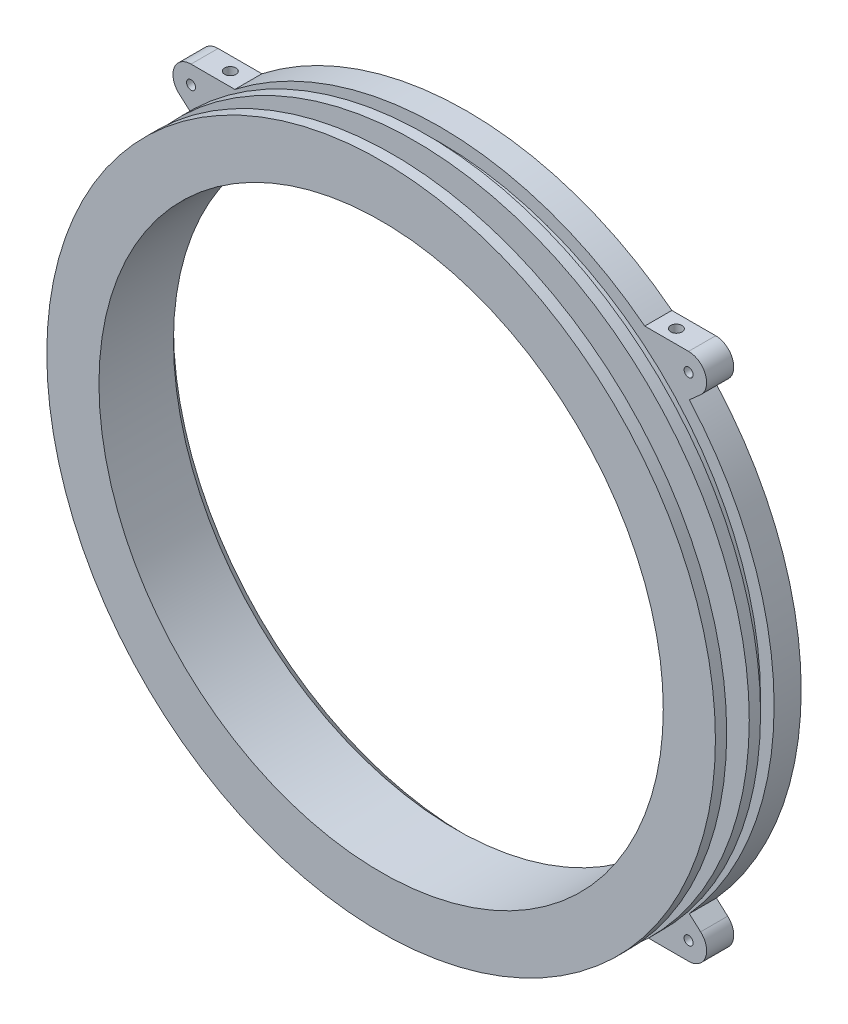
SolidWorks part; units mm, degrees
ref_plane "前视基准面" through (0, 0, 0) normal (0, 0, 1) x (1, 0, 0)
ref_plane "上视基准面" through (0, 0, 0) normal (0, 1, 0) x (1, 0, 0)
ref_plane "右视基准面" through (0, 0, 0) normal (1, 0, 0) x (0, 0, -1)
sketch "草图1" plane through (0, 0, 0) normal (0, 0, 1) x (1, 0, 0)
  circle A0 centre (0, 0) radius 148.1
  circle A1 centre (0, 0) radius 125
  dimension "D1" = 296.2
  dimension "D2" = 250
extrude "凸台-拉伸1" add sketch "草图1" along normal blind 12
sketch "草图2" plane through (0, 0, 12) normal (0, 0, 1) x (1, 0, 0)
  circle A0 centre (0, 0) radius 125
  circle A1 centre (0, 0) radius 142.1
  circle A2 centre (0, 0) radius 125 construction
  circle A3 centre (0, 0) radius 148.1 construction
  dimension "D1" = 6
extrude "凸台-拉伸2" add sketch "草图2" along normal blind 6
sketch "草图3" plane through (0, 0, 18) normal (0, 0, 1) x (1, 0, 0)
  circle A0 centre (0, 0) radius 125
  circle A1 centre (0, 0) radius 148.1
  circle A2 centre (0, 0) radius 125 construction
  circle A3 centre (0, 0) radius 148.1 construction
extrude "凸台-拉伸3" add sketch "草图3" along normal blind 5
sketch "草图4" plane through (0, 0, 23) normal (0, 0, 1) x (1, 0, 0)
  circle A0 centre (0, 0) radius 125
  circle A1 centre (0, 0) radius 133.1
  circle A2 centre (0, 0) radius 148.1 construction
  circle A4 centre (0, 0) radius 125 construction
  dimension "D1" = 15
extrude "凸台-拉伸4" add sketch "草图4" along normal blind 10
sketch "草图5" plane through (0, 0, 33) normal (0, 0, 1) x (1, 0, 0)
  circle A0 centre (0, 0) radius 125
  circle A1 centre (0, 0) radius 148.1
  circle A2 centre (0, 0) radius 125 construction
  circle A3 centre (0, 0) radius 148.1 construction
extrude "凸台-拉伸5" add sketch "草图5" along normal blind 5
sketch "草图6" plane through (0, 0, 0) normal (0, 0, 1) x (1, 0, 0)
  line L0 (-90.7998, 117) -> (-110.2082, 117)
  line L1 (-115.5327, 103.0293) -> (-110.5327, 98.5704)
  line L2 (0, 35.2925) -> (0, -26.8494) construction
  line L3 (-23.0779, 0) -> (26.357, 0) construction
  line L4 (115.5327, 103.0293) -> (110.5327, 98.5704)
  line L5 (90.7998, 117) -> (110.2082, 117)
  line L6 (115.5327, -103.0293) -> (110.5327, -98.5704)
  line L7 (90.7998, -117) -> (110.2082, -117)
  line L8 (-115.5327, -103.0293) -> (-110.5327, -98.5704)
  line L9 (-90.7998, -117) -> (-110.2082, -117)
  circle A0 centre (0, 0) radius 148.1 construction
  arc A1 (-110.2082, 117) -> (-115.5327, 103.0293) centre (-110.2082, 109) ccw
  arc A2 (-110.5327, 98.5704) -> (-90.7998, 117) centre (0, 0) cw
  circle A3 centre (-110.2082, 109) radius 2
  circle A4 centre (110.2082, 109) radius 2
  arc A5 (110.5327, 98.5704) -> (90.7998, 117) centre (0, 0) ccw
  arc A6 (110.2082, 117) -> (115.5327, 103.0293) centre (110.2082, 109) cw
  circle A7 centre (110.2082, -109) radius 2
  arc A8 (110.2082, -117) -> (115.5327, -103.0293) centre (110.2082, -109) ccw
  arc A9 (110.5327, -98.5704) -> (90.7998, -117) centre (0, 0) cw
  circle A10 centre (-110.2082, -109) radius 2
  arc A11 (-110.5327, -98.5704) -> (-90.7998, -117) centre (0, 0) ccw
  arc A12 (-110.2082, -117) -> (-115.5327, -103.0293) centre (-110.2082, -109) cw
  dimension "D1" = 4
  dimension "D2" = 8
  dimension "D3" = 5
  dimension "D4" = 117
extrude "凸台-拉伸6" add sketch "草图6" along normal blind 12
sketch "草图7" plane through (0, 117, 0) normal (0, 1, 0) x (1, 0, 0)
  line L0 (-90.7998, 0) -> (-110.2082, 0) construction
  line L2 (-90.7998, -12) -> (-90.7998, 0) construction
  circle A0 centre (-98.7998, -6) radius 2.5
  dimension "D1" = 5
  dimension "D2" = 6
  dimension "D3" = 8
extrude "切除-拉伸1" cut sketch "草图7" against normal blind 15
cosmetic thread "装饰螺纹线1" parameters "D2"=6
mirror "镜向1" about plane through (0, 0, 0) normal (1, 0, 0) of "切除-拉伸1"
mirror "镜向2" about plane through (0, 0, 0) normal (0, 1, 0) of "镜向1", "切除-拉伸1"
chamfer "倒角1" distance 5 angle 45 1 edges at (125, 0, 0)
